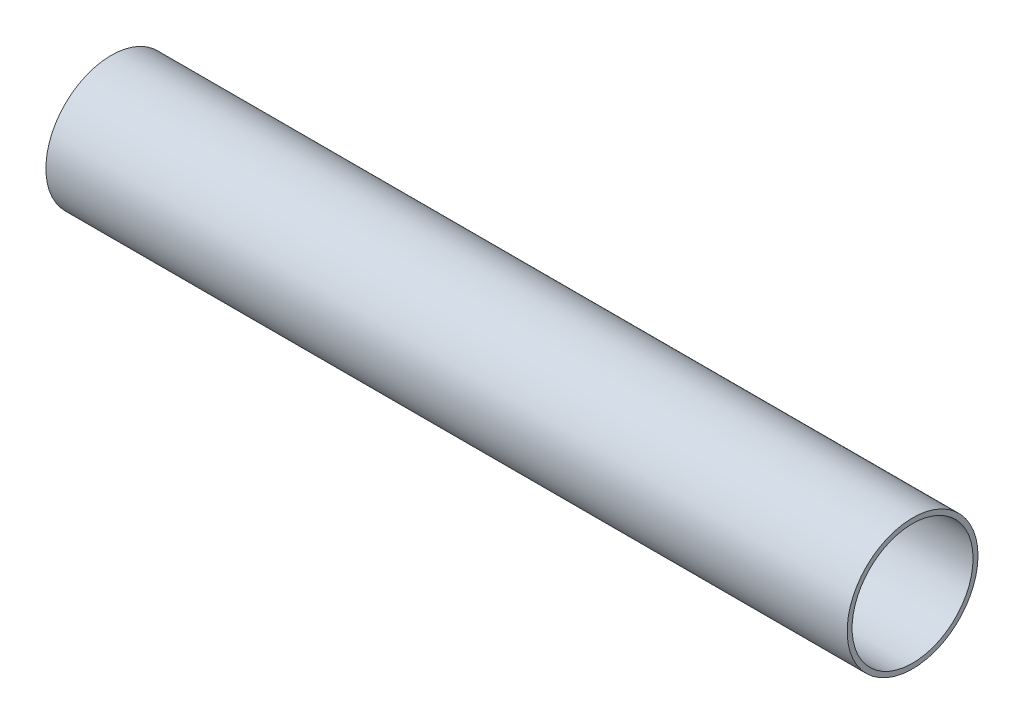
SolidWorks part; units mm, degrees
material "Silicon Rubber"
ref_plane "Front Plane" through (0, 0, 0) normal (0, 0, 1) x (1, 0, 0)
ref_plane "Top Plane" through (0, 0, 0) normal (0, 1, 0) x (1, 0, 0)
ref_plane "Right Plane" through (0, 0, 0) normal (1, 0, 0) x (0, 0, -1)
sketch "Sketch1" plane through (0, 0, 0) normal (1, 0, 0) x (0, 0, -1)
  circle A0 centre (0, 0) radius 15.875
  circle A1 centre (0, 0) radius 17.1714
  dimension "D1" = 34.3429
  dimension "D2" = 31.75
extrude "Boss-Extrude1" add sketch "Sketch1" along normal mid plane 210.312
equation "\"D1@Sketch1\"=sqr((1.25)^2+(1.125)^2-1)"
